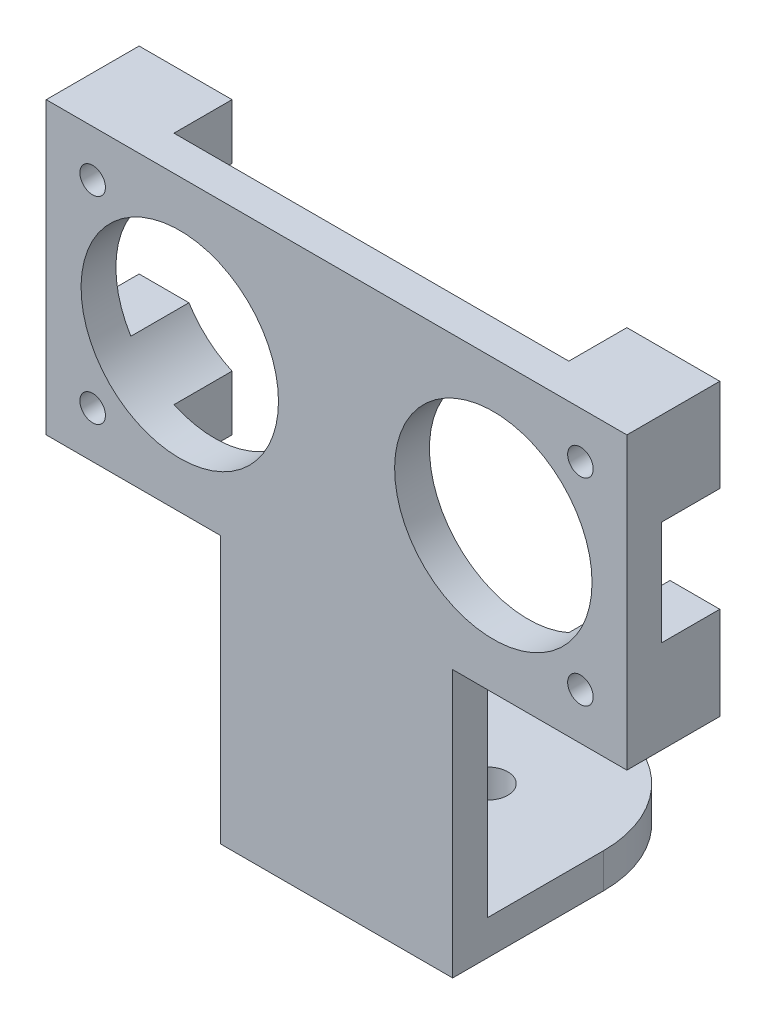
SolidWorks part; units mm, degrees
ref_plane "前视基准面" through (0, 0, 0) normal (0, 0, 1) x (1, 0, 0)
ref_plane "上视基准面" through (0, 0, 0) normal (0, 1, 0) x (1, 0, 0)
ref_plane "右视基准面" through (0, 0, 0) normal (1, 0, 0) x (0, 0, -1)
sketch "草图1" plane through (0, 0, 0) normal (0, 0, 1) x (1, 0, 0)
  line L0 (13.5, 0) -> (-13.5, 0) construction
  line L1 (-25, 12.5) -> (25, 12.5)
  line L2 (-25, 12.5) -> (-25, -12.5)
  line L3 (-25, -12.5) -> (-10, -12.5)
  line L4 (25, 12.5) -> (25, -12.5)
  line L5 (-25, 12.5) -> (25, -12.5) construction
  line L6 (-25, -12.5) -> (25, 12.5) construction
  line L8 (-10, -12.5) -> (-10, -32.5)
  line L9 (-10, -32.5) -> (10, -32.5)
  line L10 (10, -32.5) -> (10, -12.5)
  line L11 (0, 13.0132) -> (0, -46.5829) construction
  line L12 (10, -12.5) -> (25, -12.5)
  line L13 (-21, 8.5) -> (21, 8.5) construction
  line L14 (-21, 8.5) -> (-21, -8.5) construction
  line L15 (-21, -8.5) -> (21, -8.5) construction
  line L16 (21, 8.5) -> (21, -8.5) construction
  line L17 (-21, 8.5) -> (21, -8.5) construction
  line L18 (-21, -8.5) -> (21, 8.5) construction
  circle A2 centre (-13.5, 0) radius 8.5
  circle A3 centre (13.5, 0) radius 8.5
  circle A4 centre (-21, 8.5) radius 1.1
  circle A5 centre (21, 8.5) radius 1.1
  circle A6 centre (21, -8.5) radius 1.1
  circle A7 centre (-21, -8.5) radius 1.1
  point P0 (0, 0)
  point P9 (0, 0)
  point P11 (-5, 0)
  point P18 (0, 0)
  point P20 (5, 0)
  point P21 (0, 0)
  dimension "D3" = 17
  dimension "D6" = 42
  dimension "D4" = 17
  dimension "D10" = 2.2
  dimension "D1" = 25
  dimension "D2" = 50
  dimension "D5" = 10
  dimension "D7" = 20
  dimension "D8" = 20
  dimension "D9" = 17
extrude "凸台-拉伸1" add sketch "草图1" along normal blind 3
sketch "草图2" plane through (0, -32.5, 0) normal (0, -1, 0) x (1, 0, 0)
  line L0 (-10, 3) -> (-10, -10)
  line L1 (-10, 3) -> (10, 3)
  line L2 (-10, 3) -> (10, 3) construction
  line L3 (10, 3) -> (10, -10)
  line L4 (10, -10) -> (-10, -10) construction
  arc A1 (-10, -10) -> (10, -10) centre (0, -10) ccw
  circle A2 centre (0, -10) radius 1.75
  dimension "D2" = 3.5
  dimension "D1" = 13
extrude "凸台-拉伸2" add sketch "草图2" along normal blind 3
sketch "草图5" plane through (0, 0, 0) normal (0, 0, -1) x (-1, 0, 0)
  line L1 (-25, 12.5) -> (-17, 12.5)
  line L2 (-25, 12.5) -> (-25, 4.5)
  line L3 (-25, 4.5) -> (-20.7111, 4.5)
  line L4 (-17, 12.5) -> (-17, 7.746)
  line L5 (-25, -12.5) -> (-17, -12.5)
  line L6 (-25, -12.5) -> (-25, -4.5)
  line L7 (-25, -4.5) -> (-20.7111, -4.5)
  line L8 (-17, -12.5) -> (-17, -7.746)
  line L9 (25, 12.5) -> (17, 12.5)
  line L10 (25, 12.5) -> (25, 4.5)
  line L11 (25, 4.5) -> (20.7111, 4.5)
  line L12 (17, 12.5) -> (17, 7.746)
  line L13 (25, -12.5) -> (17, -12.5)
  line L14 (25, -12.5) -> (25, -4.5)
  line L15 (25, -4.5) -> (20.7111, -4.5)
  line L16 (17, -12.5) -> (17, -7.746)
  circle A0 centre (21, -8.5) radius 1.1 construction
  circle A1 centre (21, 8.5) radius 1.1 construction
  circle A2 centre (-21, -8.5) radius 1.1 construction
  circle A3 centre (-21, 8.5) radius 1.1 construction
  circle A4 centre (21, -8.5) radius 1.1
  circle A5 centre (21, 8.5) radius 1.1
  circle A6 centre (-21, -8.5) radius 1.1
  circle A7 centre (-21, 8.5) radius 1.1
  circle A8 centre (13.5, 0) radius 8.5 construction
  circle A9 centre (-13.5, 0) radius 8.5 construction
  arc A10 (17, -7.746) -> (20.7111, -4.5) centre (13.5, 0) ccw
  arc A11 (-20.7111, -4.5) -> (-17, -7.746) centre (-13.5, 0) ccw
  arc A12 (-17, 7.746) -> (-20.7111, 4.5) centre (-13.5, 0) ccw
  arc A13 (20.7111, 4.5) -> (17, 7.746) centre (13.5, 0) ccw
  dimension "D1" = 8
  dimension "D2" = 8
  dimension "D3" = 8
  dimension "D4" = 8
  dimension "D5" = 8
  dimension "D6" = 8
  dimension "D7" = 8
  dimension "D8" = 8
extrude "凸台-拉伸3" add sketch "草图5" along normal blind 5
